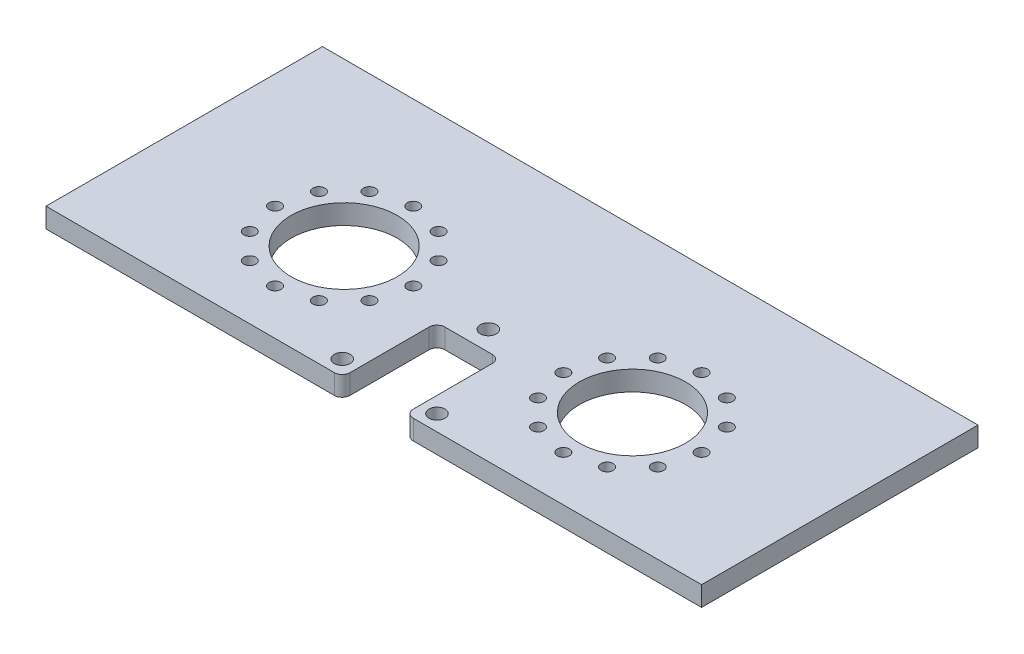
SolidWorks part; units mm, degrees
material "Thornel Mat VMA"
ref_plane "前视基准面" through (0, 0, 0) normal (0, 0, 1) x (1, 0, 0)
ref_plane "上视基准面" through (0, 0, 0) normal (0, 1, 0) x (1, 0, 0)
ref_plane "右视基准面" through (0, 0, 0) normal (1, 0, 0) x (0, 0, -1)
other "Configuration Table"
sketch "草图1" plane through (0, 0, 0) normal (0, 1, 0) x (1, 0, 0)
  line L1 (-83, -35) -> (83, -35)
  line L2 (-83, -35) -> (-83, 35)
  line L3 (-83, 35) -> (83, 35)
  line L4 (83, -35) -> (83, 35)
  line L5 (-83, -35) -> (83, 35) construction
  line L6 (-83, 35) -> (83, -35) construction
  point P0 (0, 0)
  dimension "D1" = 166
  dimension "D2" = 70
extrude "凸台-拉伸1" add sketch "草图1" along normal blind 5
sketch "草图2" plane through (0, 0, 0) normal (0, -1, 0) x (1, 0, 0)
  circle A0 centre (12, 31) radius 1.65 construction
  circle A1 centre (0, 6) radius 1.65 construction
  circle A2 centre (-12, 31) radius 1.65 construction
  circle A3 centre (12, 31) radius 1.65 construction
  circle A4 centre (0, 6) radius 1.65 construction
  circle A5 centre (-12, 31) radius 1.65 construction
  circle A6 centre (-12, 31) radius 2.025
  circle A7 centre (12, 31) radius 2.025
  circle A8 centre (0, 6) radius 2.025
  dimension "D1" = 4.05
extrude "切除-拉伸1" cut sketch "草图2" against normal blind 5
sketch "草图3" plane through (0, 0, 0) normal (0, -1, 0) x (1, 0, 0)
  circle A8 centre (36.5, 6) radius 30 construction
  circle A9 centre (-36.5, 6) radius 30 construction
  circle A10 centre (36.5, 6) radius 30 construction
  circle A11 centre (-36.5, 6) radius 30 construction
  circle A12 centre (36.5, 6) radius 17.5 construction
  circle A13 centre (-36.5, 6) radius 17.5 construction
  circle A14 centre (36.5, 23.5) radius 1.525
  circle A15 centre (45.25, 21.1554) radius 1.525
  circle A16 centre (51.6554, 14.75) radius 1.525
  circle A17 centre (54, 6) radius 1.525
  circle A18 centre (51.6554, -2.75) radius 1.525
  circle A19 centre (45.25, -9.1554) radius 1.525
  circle A20 centre (36.5, -11.5) radius 1.525
  circle A21 centre (27.75, -9.1554) radius 1.525
  circle A22 centre (21.3446, -2.75) radius 1.525
  circle A23 centre (19, 6) radius 1.525
  circle A24 centre (21.3446, 14.75) radius 1.525
  circle A25 centre (27.75, 21.1554) radius 1.525
  circle A26 centre (36.5, 6) radius 13.45
  point P34 (36.5, 6)
  dimension "D1" = 35
  dimension "D2" = 3.05
  dimension "D4" = 26.9
  dimension "D3" = 12
extrude "切除-拉伸2" cut sketch "草图3" against normal blind 81.4
mirror "镜向1" about plane through (0, 0, 0) normal (1, 0, 0) of "切除-拉伸2"
sketch "草图5" plane through (0, 0, 0) normal (0, -1, 0) x (1, 0, 0)
  line L0 (-83, 35) -> (83, 35) construction
  line L1 (-8, 11) -> (8, 11)
  line L2 (-8, 11) -> (-8, 59)
  line L3 (-8, 59) -> (8, 59)
  line L4 (8, 11) -> (8, 59)
  line L5 (-8, 11) -> (8, 59) construction
  line L6 (-8, 59) -> (8, 11) construction
  circle A0 centre (12, 31) radius 2.025 construction
  circle A1 centre (0, 6) radius 2.025 construction
  point P0 (0, 35)
  dimension "D1" = 4
  dimension "D2" = 5
extrude "切除-拉伸4" cut sketch "草图5" against normal blind 81.4
fillet "圆角2" radius 2 4 edges at (8, 2.5, 35) (8, 2.5, 11) (-8, 2.5, 35) (-8, 2.5, 11)
